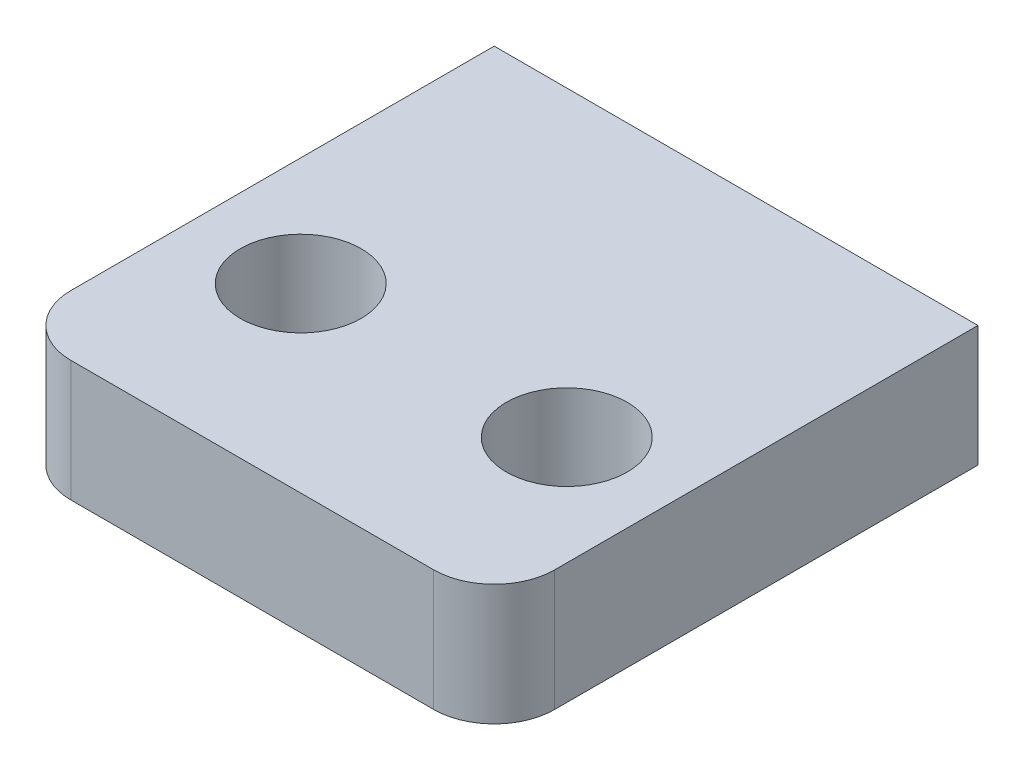
SolidWorks part; units mm, degrees
ref_plane "Alzado" through (0, 0, 0) normal (0, 0, 1) x (1, 0, 0)
ref_plane "Planta" through (0, 0, 0) normal (0, 1, 0) x (1, 0, 0)
ref_plane "Vista lateral" through (0, 0, 0) normal (1, 0, 0) x (0, 0, -1)
sketch "Croquis2" plane through (0, 0, 0) normal (0, 1, 0) x (1, 0, 0)
  line L1 (-64.624, 39.2201) -> (15.376, 39.2201)
  line L2 (-64.624, 39.2201) -> (-64.624, -40.7799)
  line L3 (-64.624, -40.7799) -> (15.376, -40.7799)
  line L4 (15.376, 39.2201) -> (15.376, -40.7799)
  dimension "D1" = 80
  dimension "D2" = 80
extrude "Saliente-Extruir1" add sketch "Croquis2" along normal blind 20
fillet "Redondeo1" radius 10 1 edges at (15.376, 10, 40.7799)
fillet "Redondeo2" radius 10 1 edges at (-64.624, 10, 40.7799)
sketch "Croquis3" plane through (0, 20, 0) normal (0, 1, 0) x (1, 0, 0)
  line L0 (-64.624, 39.2201) -> (-64.624, -30.7799) construction
  line L1 (-54.624, -40.7799) -> (5.376, -40.7799) construction
  circle A0 centre (-46.624, -10.7799) radius 10
  circle A1 centre (-2.624, -10.7799) radius 10
  dimension "D3" = 20
  dimension "D1" = 18
  dimension "D2" = 30
extrude "Cortar-Extruir1" cut sketch "Croquis3" against normal through all contours A0 | A1
